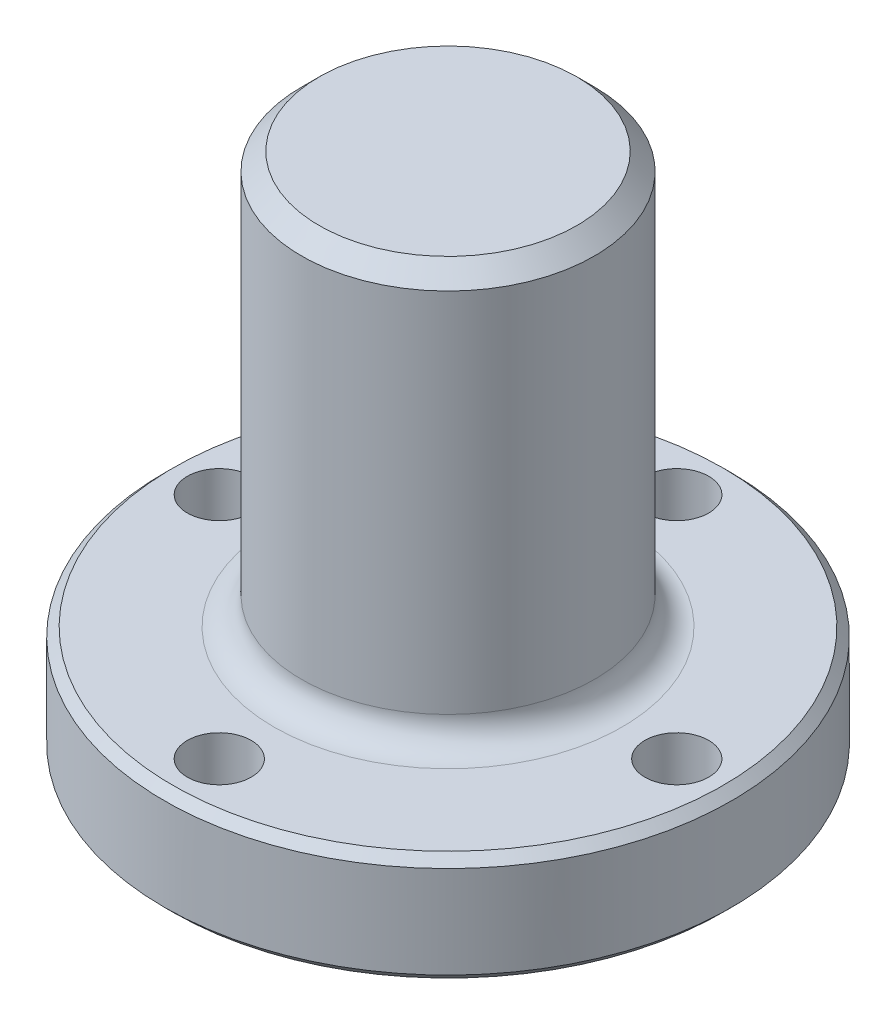
SolidWorks part; units mm, degrees
ref_plane "Front Plane" through (0, 0, 0) normal (1, 0, 0) x (0, 1, 0)
ref_plane "Top Plane" through (0, 0, 0) normal (0, 0, 1) x (0, 1, 0)
ref_plane "Right Plane" through (0, 0, 0) normal (0, 1, 0) x (-1, 0, 0)
sketch "Sketch1" plane through (0, 0, 0) normal (0, 0, 1) x (0, 1, 0)
  line L0 (-25.0317, 0) -> (-25.0317, 8.7122)
  line L1 (-25.0317, 8.7122) -> (-20.2057, 8.7122)
  line L2 (-20.2057, 8.7122) -> (-20.2057, 24.6126)
  line L3 (-20.2057, 24.6126) -> (-10.6807, 24.6126)
  line L4 (-10.6807, 24.6126) -> (-10.6807, 12.7)
  line L5 (-10.6807, 12.7) -> (25.0317, 12.7)
  line L6 (25.0317, 12.7) -> (25.0317, 0)
  line L7 (25.0317, 0) -> (-25.0317, 0)
  line L8 (-50.4317, 0) -> (50.4317, 0) construction
  dimension "D1" = 35.7124
  dimension "D2" = 45.2374
  dimension "D3" = 50.0634
  dimension "D4" = 11.9126
  dimension "D5" = 15.9004
  dimension "D6" = 24.6126
revolve "Revolve1" add sketch "Sketch1" angle 360 about L8
sketch "Sketch2" plane through (0, 0, 0) normal (0, 1, 0) x (-1, 0, 0)
  circle A0 centre (19.8374, 0) radius 2.7686
  circle A1 centre (0, 19.8374) radius 2.7686
  circle A2 centre (-19.8374, 0) radius 2.7686
  circle A3 centre (0, -19.8374) radius 2.7686
  dimension "D1" = 5.5372
  dimension "D2" = 5.5372
  dimension "D3" = 5.5372
  dimension "D4" = 5.5372
  dimension "D5" = 19.8374
  dimension "D6" = 19.8374
  dimension "D7" = 39.6748
  dimension "D8" = 19.8374
  dimension "D9" = 19.8374
  dimension "D10" = 39.6748
extrude "Cut-Extrude2" cut sketch "Sketch2" along normal blind 20.2057 from offset 20.2057
fillet "Fillet1" radius 2.3876 1 edges at (0, -10.6807, -12.7)
chamfer "Chamfer1" distance 0.762 angle 45 2 edges at (0, -10.6807, -24.6126) (0, -20.2057, -24.6126)
chamfer "Chamfer2" distance 1.524 angle 45 1 edges at (0, 25.0317, -12.7)
